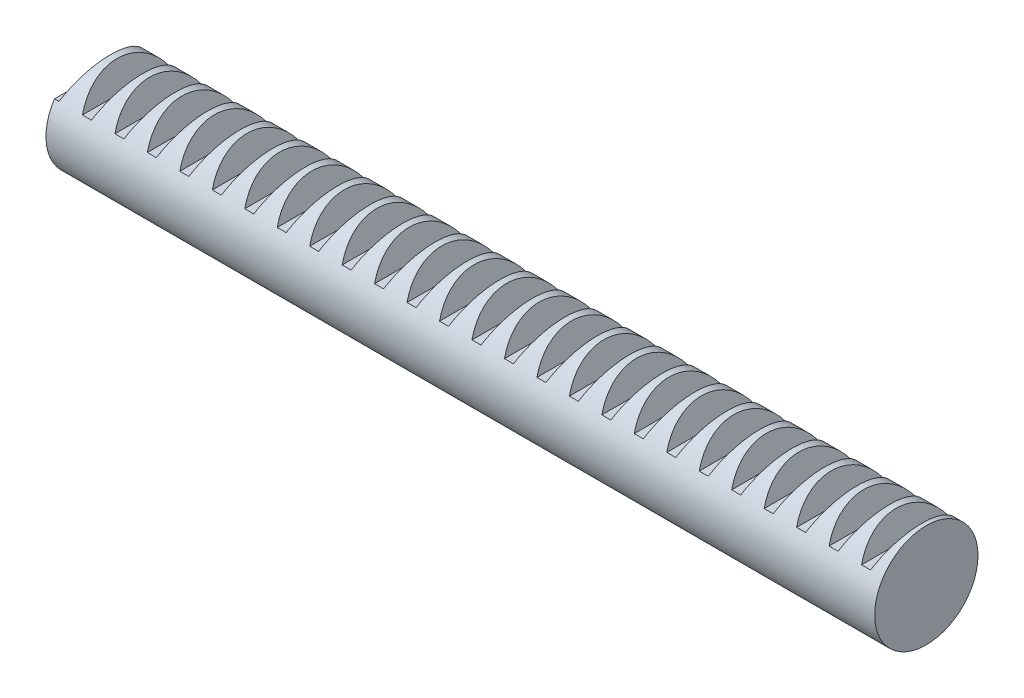
SolidWorks part; units mm, degrees
extrude "Blank" add sketch "BlankSke" against normal blind 25
sketch "BlankSke" plane through (0, 0, 0) normal (0, 0, 1) x (1, 0, 0)
  line L1 (0, 0) -> (500, 0)
  line L2 (0, 0) -> (0, 27.5)
  line L3 (0, 27.5) -> (500, 27.5)
  line L4 (500, 0) -> (500, 27.5)
  dimension "Length" = 500
  dimension "Blank_height" = 27.5
ref_plane "Plane1" through (0, 0, 0) normal (0, 0, 1) x (1, 0, 0)
ref_plane "Plane2" through (0, 0, 0) normal (0, 1, 0) x (1, 0, 0)
ref_plane "Plane3" through (0, 0, 0) normal (1, 0, 0) x (0, 0, -1)
sketch "HoldingSke" plane through (0, 0, 0) normal (0, 1, 0) x (1, 0, 0)
  line L0 (0, 0) -> (0.0557, 0.3961)
  line L1 (-15, 0) -> (100, 0) construction
  line L2 (0, 0) -> (-2.1039, 2.3779)
  line L3 (0, 0) -> (-11.863, 4.5341)
  line L4 (0, 0) -> (3.6497, 7.8269)
  line L5 (0, 0) -> (-23.7986, -8.8762)
  line L6 (0, 0) -> (-10.5278, -7.1032)
  line L9 (-71.009, 38.7566) -> (398.8373, 209.7667)
  line L10 (-76.2, 4.8779) -> (-51.2, 4.8779)
  line L11 (0, 0) -> (-25, 0)
  line L12 (-76.2, 101.6) -> (-76.113, 101.6)
  line L13 (24.9733, 27.94) -> (52.9518, 28.4284)
  line L14 (24.9733, 27.94) -> (24.9743, 27.94)
  line L15 (24.9733, 27.94) -> (100.4006, 29.5858)
  circle A0 centre (0, 0) radius 19.05
  circle A1 centre (0, 0) radius 12.5
  circle A2 centre (0, 0) radius 12.7
  dimension "MPH" = 25
  dimension "Diameter" = 38.1
  dimension "Num_teeth" = 65
  dimension "Pitch" = 0.4
  dimension "Show_teeth" = 998
  dimension "Thickness" = 12.7
  dimension "Ap" = 20
  dimension "Pitch_height" = 25
  dimension "Width" = 25
  dimension "Backlash" = 0.087
  dimension "Addendum_fac" = 1
  dimension "Dedendum_fac" = 1.25
  dimension "Clearance_fac" = 0.25
  dimension "Dedendum_add" = 0.001
  dimension "Length" = 500
  dimension "Module" = 2.5
sketch "TooCutSkeIll" plane through (0, 0, 0) normal (0, 0, 1) x (1, 0, 0)
  line L0 (-3.1105, 27.4342) -> (-1.237, 22.2869)
  line L1 (-0.6488, 21.875) -> (0.6488, 21.875)
  line L2 (1.237, 22.2869) -> (3.1105, 27.4342)
  line L3 (500, 27.5) -> (0, 27.5) construction
  line L4 (0, 0) -> (0, 64.897) construction
  line L5 (-13.208, 25) -> (12.954, 25) construction
  line L6 (0, 0) -> (500, 0) construction
  line L7 (2.2245, 25) -> (2.2245, 48.7463) construction
  line L8 (-2.2245, 25) -> (-2.2245, 48.7463) construction
  line L9 (3.2044, 27.5) -> (3.2044, 27.5254)
  line L10 (-3.2044, 27.5) -> (-3.2044, 27.5254)
  line L11 (-3.2044, 27.5254) -> (3.2044, 27.5254)
  arc A0 (0.6488, 21.875) -> (1.237, 22.2869) centre (0.6488, 22.501) ccw
  arc A1 (-1.237, 22.2869) -> (-0.6488, 21.875) centre (-0.6488, 22.501) ccw
  arc A2 (3.2044, 27.5) -> (3.1105, 27.4342) centre (3.2044, 27.4) ccw
  arc A3 (-3.1105, 27.4342) -> (-3.2044, 27.5) centre (-3.2044, 27.4) ccw
  dimension "Pitch_height" = 25
  dimension "Addendum_plus" = 2.5254
  dimension "Pressure_angle" = 20
  dimension "Gap_width" = 4.449
  dimension "Dedendum" = 3.125
sketch "TooCutSkeSim" plane through (0, 0, 0) normal (0, 0, 1) x (1, 0, 0)
  line L0 (1.0871, 21.875) -> (-1.0871, 21.875)
  line L1 (3.1437, 27.5254) -> (1.0871, 21.875)
  line L2 (0, 17.4625) -> (0, 53.467) construction
  line L3 (3.1437, 27.5254) -> (-3.1437, 27.5254)
  line L6 (-3.1437, 27.5254) -> (-1.0871, 21.875)
  line L9 (-2.2245, 25) -> (2.2245, 25) construction
  line L10 (0, 0) -> (500, 0) construction
  line L11 (2.2245, 25) -> (2.2245, 53.467) construction
  line L12 (-2.2245, 25) -> (-2.2245, 53.467) construction
  dimension "Pitch_height" = 25
  dimension "Addendum_plus" = 2.5254
  dimension "Pressure_angle" = 20
  dimension "Gap_width" = 4.449
  dimension "Dedendum" = 3.125
extrude "ToothCutSim" cut sketch "TooCutSkeSim" against normal through all
pattern_linear "TeethCuts" count 64 spacing 7.854 along (1, 0, 0) of "ToothCutSim"
sketch "Sketch1" plane through (0, 0, 0) normal (0, -1, 0) x (1, 0, 0)
  line L1 (0, 0) -> (500, 0)
  line L2 (0, 0) -> (0, -25)
  line L3 (0, -25) -> (500, -25)
  line L4 (500, 0) -> (500, -25)
extrude "Cut-Extrude1" cut sketch "Sketch1" against normal blind 2.5
sketch "Sketch2" plane through (500, 0, 0) normal (1, 0, 0) x (0, 0, -1)
  line L1 (0, 2.5) -> (25, 2.5)
  line L2 (0, 2.5) -> (0, 27.5)
  circle A0 centre (12.5, 15) radius 12.5
  circle A1 centre (12.5, 15) radius 21.615
extrude "Cut-Extrude2" cut sketch "Sketch2" against normal blind 566.5
ref_plane "Plane4" through (0, 0, -12.5) normal (0, 0, 1) x (1, 0, 0)
extrude "Cut-Extrude3" cut sketch "Sketch3" against normal blind 299.5
sketch "Sketch3" plane through (500, 66.0814, 9.3901) normal (1, 0, 0) x (0, 0, 1)
  circle A0 centre (-21.8901, 51.0814) radius 12.55
equation "' \"Module@HoldingSke\" = 6.35"
equation "' \"Num_teeth@HoldingSke\" = 12"
equation "' \"Ap@HoldingSke\" =  20"
equation "' \"Ap@HoldingSke\" = 20"
equation "' \"Width@HoldingSke\" = 0.25 * 25.4"
equation "' \"Show_teeth@HoldingSke\" = 500"
equation "' \"Backlash@HoldingSke\" = 0.009 * 25.4"
equation "' \"Addendum_fac@HoldingSke\" = 1.0"
equation "' \"Dedendum_fac@HoldingSke\" = 1.25"
equation "' \"Dedendum_add@HoldingSke\" = 0.00005 * 25.4"
equation "' \"Clearance_fac@HoldingSke\" = 0.25"
equation "' \"Pitch_height@HoldingSke\" = 1 * 25.4"
equation "' \"Length@HoldingSke\" = 4.71 * 25.4"
equation "\"Pitch@HoldingSke\" = 1 / \"Module@HoldingSke\""
equation "\"MPH@HoldingSke\" = \"Dedendum_fac@HoldingSke\" / \"Pitch@HoldingSke\" + 2 * \"Dedendum_add@HoldingSke\" + 0.002 * 25.4"
equation "\"MPH@HoldingSke\" = ((sgn( \"MPH@HoldingSke\" - \"Pitch_height@HoldingSke\")+1)*( \"MPH@HoldingSke\" - \"Pitch_height@HoldingSke\"))/2 + \"Pitch_height@HoldingSke\""
equation "\"Blank_height@BlankSke\" = \"Pitch_height@HoldingSke\" + \"Addendum_fac@HoldingSke\"  / \"Pitch@HoldingSke\" "
equation "\"Length@BlankSke\" =  \"Length@HoldingSke\""
equation "\"Face_width@Blank\" = \"Width@HoldingSke\""
equation "\"Pressure_angle@TooCutSkeIll\" = \"Ap@HoldingSke\""
equation "\"Addendum_plus@TooCutSkeIll\" =  \"Addendum_fac@HoldingSke\"  / \"Pitch@HoldingSke\" + 0.001 *25.4"
equation "\"Dedendum@TooCutSkeIll\" = \"Dedendum_fac@HoldingSke\"  / \"Pitch@HoldingSke\""
equation "\"Pitch_height@TooCutSkeIll\" =  \"MPH@HoldingSke\""
equation "\"Gap_width@TooCutSkeIll\" = 3.14159265 / 2 / \"Pitch@HoldingSke\" + 6 * \"Backlash@HoldingSke\""
equation "\"Pressure_angle@TooCutSkeSim\" = \"Ap@HoldingSke\""
equation "\"Addendum_plus@TooCutSkeSim\" =  \"Addendum_fac@HoldingSke\"  / \"Pitch@HoldingSke\" + 0.001 * 25.4"
equation "\"Dedendum@TooCutSkeSim\" = \"Dedendum_fac@HoldingSke\"  / \"Pitch@HoldingSke\""
equation "\"Pitch_height@TooCutSkeSim\" =  \"MPH@HoldingSke\""
equation "\"Gap_width@TooCutSkeSim\" = 3.14159265 / 2 / \"Pitch@HoldingSke\" + 6 * \"Backlash@HoldingSke\""
equation "\"Root_fillet@TooCutSkeIll\" = \"Clearance_fac@HoldingSke\" / \"Pitch@HoldingSke\" + \"Dedendum_add@HoldingSke\""
equation "\"Break_rad@TooCutSkeIll\" = 0.02 / \"Pitch@HoldingSke\" * 2"
equation "\"Linear_pitch@TeethCuts\" = 3.14159265 / \"Pitch@HoldingSke\""
equation "\"Num_teeth@HoldingSke\" = int( ( \"Length@HoldingSke\" + 0 ) / (3.14159265 / \"Pitch@HoldingSke\")) + 0.9999  + 1"
equation " \"Num_teeth@TeethCuts\" = int( \"Show_teeth@HoldingSke\" ) + 1"
equation " \"Num_teeth@TeethCuts\" = ((sgn( \"Num_teeth@TeethCuts\" - \"Num_teeth@HoldingSke\" )-1)*( \"Num_teeth@TeethCuts\" - \"Num_teeth@HoldingSke\" ))/-2+ \"Num_teeth@HoldingSke\""
equation " \"Num_teeth@TeethCuts\" = ((sgn( \"Num_teeth@TeethCuts\" - 2.0)+1)*( \"Num_teeth@TeethCuts\" - 2.0))/2 +2.0"
